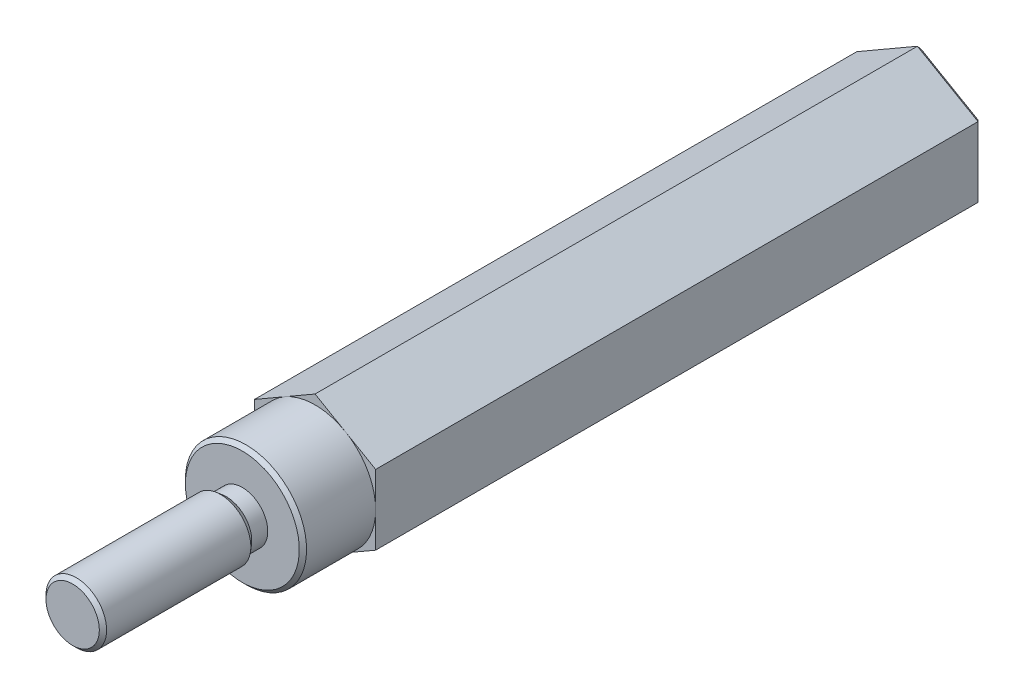
SolidWorks part; units mm, degrees
material "2.0367 (CuZn40)"
ref_plane "Vorne" through (0, 0, 0) normal (0, 0, 1) x (1, 0, 0)
ref_plane "Oben" through (0, 0, 0) normal (0, 1, 0) x (1, 0, 0)
ref_plane "Rechts" through (0, 0, 0) normal (1, 0, 0) x (0, 0, -1)
sketch "Skizze1" plane through (0, 0, 0) normal (0, 0, 1) x (1, 0, 0)
  line L1 (0, 5.7735) -> (-5, 2.8868)
  line L2 (-5, 2.8868) -> (-5, -2.8868)
  line L3 (-5, -2.8868) -> (0, -5.7735)
  line L4 (0, -5.7735) -> (5, -2.8868)
  line L5 (5, -2.8868) -> (5, 2.8868)
  line L6 (5, 2.8868) -> (0, 5.7735)
  circle A0 centre (0, 0) radius 5 construction
  dimension "D1" = 10
extrude "Aufsatz-Linear austragen1" add sketch "Skizze1" along normal blind 70
sketch "Skizze2" plane through (0, 0, 0) normal (1, 0, 0) x (0, 0, -1)
  line L0 (-70, 2.5) -> (-56, 2.5)
  line L1 (-70, -2.8868) -> (-70, 2.8868) construction
  line L2 (-56, 2.5) -> (-56, 5)
  line L3 (-56, 5) -> (-50, 5)
  line L4 (-50, 5) -> (-50, 7.5)
  line L5 (-50, 7.5) -> (-70, 7.5)
  line L6 (-70, 7.5) -> (-70, 2.5)
  line L7 (-56.7167, 0) -> (-71.3523, 0) construction
  line L8 (5.5, 0) -> (-5.5, 0) construction
  dimension "D1" = 5
  dimension "D2" = 10
  dimension "D3" = 15
  dimension "D4" = 14
  dimension "D5" = 20
revolve "Schnitt-Rotation1" cut sketch "Skizze2" angle 360 about L7
cosmetic thread "Gewindedarstellung1" parameters "D2"=4.11
chamfer "Fase1" distance 0.3 angle 45 2 edges at (-5, 0, 56) (-2.5, 0, 70)
sketch "Skizze3" plane through (0, 0, 0) normal (1, 0, 0) x (0, 0, -1)
  line L0 (-56, 2.5) -> (-57.8, 2.5)
  line L1 (-56, 2.5) -> (-69.7, 2.5) construction
  line L2 (-57.8, 2.5) -> (-57.3233, 2.1)
  line L3 (-57.3233, 2.1) -> (-56, 2.1)
  line L4 (-56, 2.5) -> (-56, -2.5) construction
  line L5 (-56, 2.1) -> (-56, 2.5)
  line L6 (-56, 0) -> (-70.8859, 0) construction
  line L7 (-56, 4.7) -> (-56, -4.7) construction
  line L8 (5.5, 0) -> (-5.5, 0) construction
  dimension "D1" = 1.8
  dimension "D2" = 0.4
  dimension "D3" = 40
revolve "Schnitt-Rotation2" cut sketch "Skizze3" angle 360 about L6
chamfer "Fase2" distance 0.3 angle 45 6 edges at (-2.5, 4.3301, 0) (-5, 0, 0) (-2.5, -4.3301, 0) (2.5, -4.3301, 0) (5, 0, 0) (2.5, 4.3301, 0)
